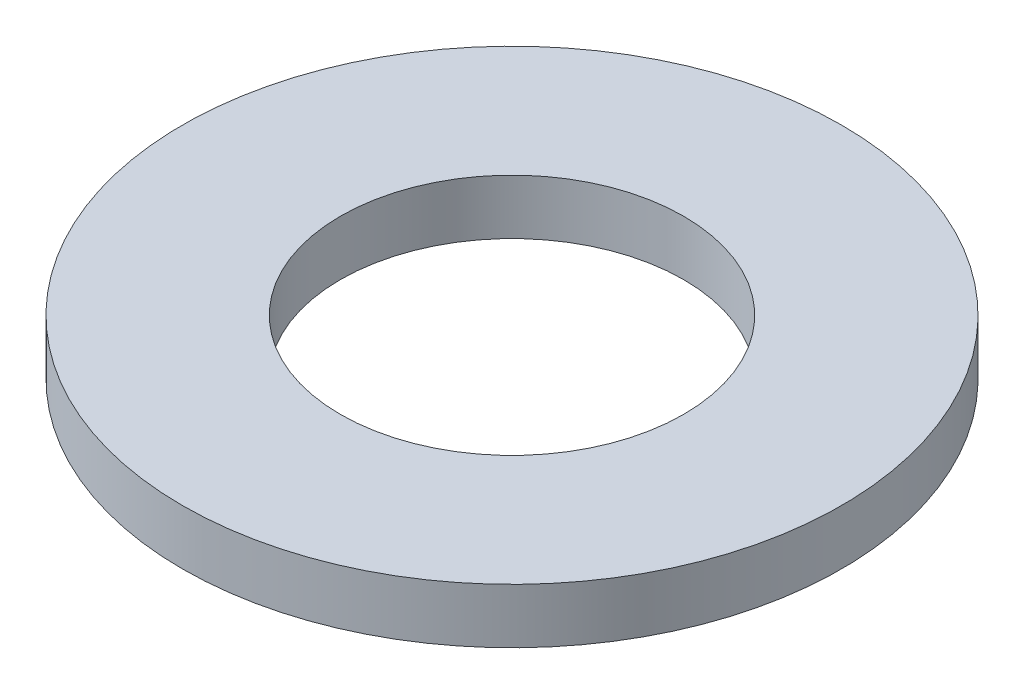
SolidWorks part; units mm, degrees
ref_plane "Front Plane" through (0, 0, 0) normal (0, 0, 1) x (1, 0, 0)
ref_plane "Top Plane" through (0, 0, 0) normal (0, 1, 0) x (1, 0, 0)
ref_plane "Right Plane" through (0, 0, 0) normal (1, 0, 0) x (0, 0, -1)
sketch "Sketch1" plane through (0, 0, 0) normal (0, 1, 0) x (1, 0, 0)
  circle A0 centre (0, 0) radius 6
  circle A1 centre (0, 0) radius 3.125
  dimension "D1" = 12
  dimension "D2" = 6.25
extrude "Boss-Extrude1" add sketch "Sketch1" along normal mid plane 1
